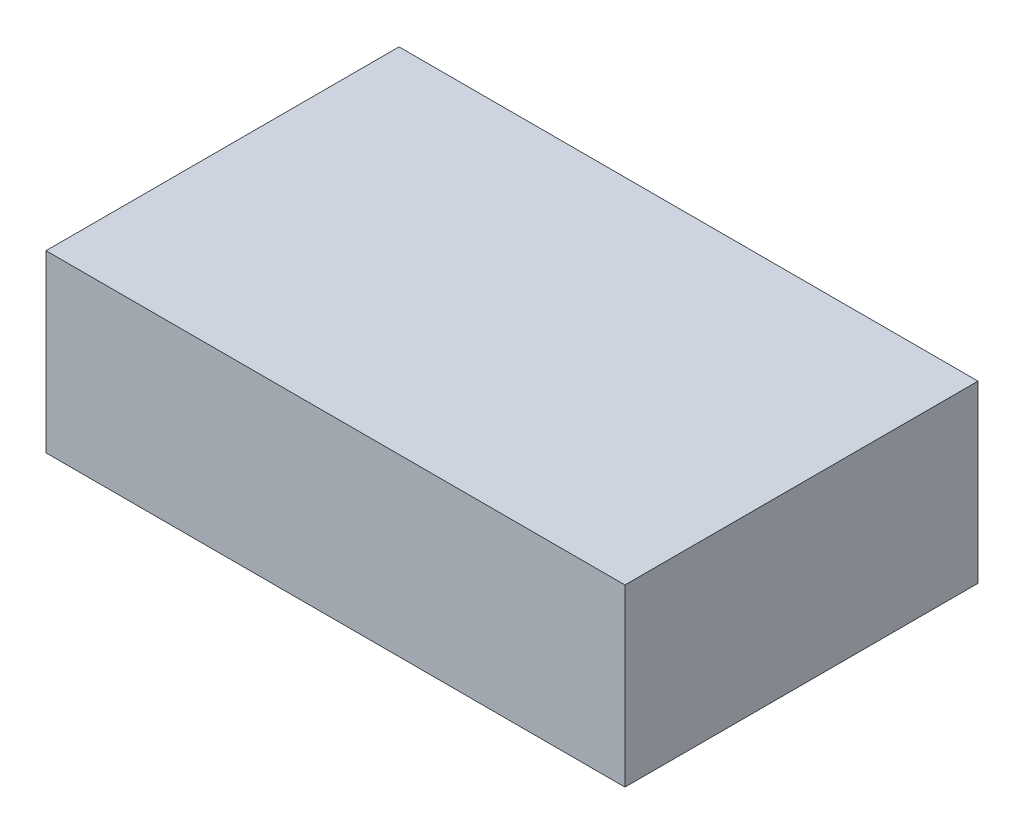
SolidWorks part; units mm, degrees
ref_plane "前视基准面" through (0, 0, 0) normal (0, 0, 1) x (1, 0, 0)
ref_plane "上视基准面" through (0, 0, 0) normal (0, 1, 0) x (1, 0, 0)
ref_plane "右视基准面" through (0, 0, 0) normal (1, 0, 0) x (0, 0, -1)
sketch "草图2" plane through (0, 0, 0) normal (0, 1, 0) x (1, 0, 0)
  line L1 (-51.25, 31.25) -> (51.25, 31.25)
  line L2 (-51.25, 31.25) -> (-51.25, -31.25)
  line L3 (-51.25, -31.25) -> (51.25, -31.25)
  line L4 (51.25, 31.25) -> (51.25, -31.25)
  line L5 (-51.25, 31.25) -> (51.25, -31.25) construction
  line L6 (-51.25, -31.25) -> (51.25, 31.25) construction
  point P0 (0, 0)
  dimension "D1" = 102.5
  dimension "D2" = 62.5
extrude "凸台-拉伸2" add sketch "草图2" along normal blind 31
sketch "草图3" plane through (0, 0, 0) normal (0, -1, 0) x (1, 0, 0)
  line L1 (-30, 20) -> (30, 20) construction
  line L2 (-30, 20) -> (-30, -20) construction
  line L3 (-30, -20) -> (30, -20) construction
  line L4 (30, 20) -> (30, -20) construction
  line L5 (-30, 20) -> (30, -20) construction
  line L6 (-30, -20) -> (30, 20) construction
  circle A0 centre (-30, 20) radius 1.25
  circle A1 centre (30, 20) radius 1.25
  circle A2 centre (30, -20) radius 1.25
  circle A3 centre (-30, -20) radius 1.25
  point P0 (0, 0)
  point P7 (0, 0)
  point P8 (0, 0)
  dimension "D3" = 2.5
  dimension "D1" = 60
  dimension "D2" = 40
  dimension "D4" = 2
  dimension "D5" = 2
extrude "切除-拉伸1" cut sketch "草图3" against normal blind 5
